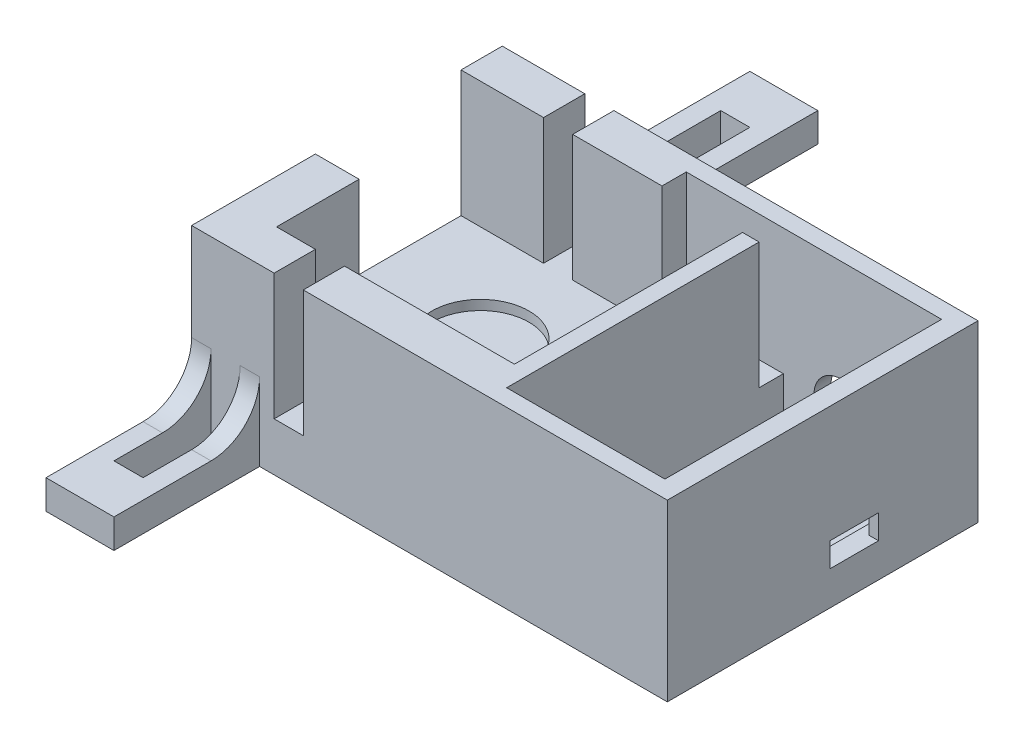
SolidWorks part; units mm, degrees
ref_plane "前视基准面" through (0, 0, 0) normal (0, 0, 1) x (1, 0, 0)
ref_plane "上视基准面" through (0, 0, 0) normal (0, 1, 0) x (1, 0, 0)
ref_plane "右视基准面" through (0, 0, 0) normal (1, 0, 0) x (0, 0, -1)
sketch "草图1" plane through (0, 0, 0) normal (0, 1, 0) x (1, 0, 0)
  line L21 (0, 0) -> (49, 0)
  line L22 (0, 0) -> (0, 32)
  line L23 (0, 32) -> (49, 32)
  line L24 (49, 0) -> (49, 32)
  dimension "D1" = 32
  dimension "D2" = 49
extrude "凸台-拉伸2" add sketch "草图1" along normal blind 18
sketch "草图6" plane through (0, 18, 0) normal (0, 1, 0) x (1, 0, 0)
  line L0 (4.5, 32) -> (4.5, 0) construction
  line L1 (49, 32) -> (0, 32) construction
  line L2 (0, 0) -> (49, 0) construction
  line L4 (4.5, 27.75) -> (29, 27.75)
  line L5 (4.5, 27.75) -> (4.5, 4.25)
  line L6 (4.5, 4.25) -> (29, 4.25)
  line L7 (29, 27.75) -> (29, 4.25)
  line L8 (49, 0) -> (49, 32) construction
  line L9 (4.5, 30) -> (47, 30) construction
  line L10 (4.5, 30) -> (4.5, 2) construction
  line L11 (4.5, 2) -> (47, 2) construction
  line L12 (47, 30) -> (47, 2) construction
  dimension "D1" = 4.5
  dimension "D2" = 23.5
  dimension "D3" = 24.5
  dimension "D4" = 2.25
  dimension "D5" = 2
  dimension "D6" = 2
  dimension "D7" = 2
extrude "切除-拉伸1" cut sketch "草图6" against normal blind 13
sketch "草图7" plane through (0, 18, 0) normal (0, 1, 0) x (1, 0, 0)
  line L0 (49, 0) -> (49, 32) construction
  line L1 (30.7, 30.25) -> (47, 30.25)
  line L2 (30.7, 30.25) -> (30.7, 1.75)
  line L3 (30.7, 1.75) -> (47, 1.75)
  line L4 (47, 30.25) -> (47, 1.75)
  line L5 (49, 32) -> (0, 32) construction
  line L6 (0, 0) -> (49, 0) construction
  dimension "D1" = 2
  dimension "D2" = 1.75
  dimension "D3" = 1.75
  dimension "D4" = 16.3
extrude "切除-拉伸2" cut sketch "草图7" against normal blind 16.5
sketch "草图8" plane through (0, 18, 0) normal (0, 1, 0) x (1, 0, 0)
  line L0 (49, 32) -> (0, 32) construction
  line L1 (8.5, 32) -> (11.5, 32)
  line L2 (8.5, 32) -> (8.5, 0)
  line L3 (8.5, 0) -> (11.5, 0)
  line L4 (11.5, 32) -> (11.5, 0)
  line L5 (0, 0) -> (49, 0) construction
  dimension "D1" = 3
  dimension "D2" = 4
extrude "切除-拉伸3" cut sketch "草图8" against normal blind 13
sketch "草图12" plane through (4.5, 0, 0) normal (1, 0, 0) x (0, 0, -1)
  line L1 (27.75, 5) -> (12.75, 5)
  line L2 (27.75, 5) -> (27.75, 18)
  line L3 (27.75, 18) -> (12.75, 18)
  line L4 (27.75, 18) -> (4.25, 18)
  line L5 (4.25, 18) -> (4.25, 5)
  line L6 (4.25, 5) -> (27.75, 5)
  line L7 (27.75, 5) -> (27.75, 18)
  line L8 (27.75, 18) -> (4.25, 18) construction
  line L9 (4.25, 18) -> (4.25, 5) construction
  line L10 (4.25, 5) -> (27.75, 5) construction
  line L11 (27.75, 5) -> (27.75, 18) construction
  line L12 (12.75, 5) -> (12.75, 18)
  dimension "D2" = 15
  dimension "D1" = 0
extrude "切除-拉伸5" cut sketch "草图12" against normal through all
sketch "草图13" plane through (0, 18, 0) normal (0, 1, 0) x (1, 0, 0)
  line L0 (29, 27.75) -> (11.5, 27.75) construction
  line L1 (30.7, 30.25) -> (20.7, 30.25)
  line L2 (30.7, 30.25) -> (30.7, 27.75)
  line L3 (30.7, 27.75) -> (20.7, 27.75)
  line L4 (20.7, 30.25) -> (20.7, 27.75)
  dimension "D1" = 10
extrude "切除-拉伸6" cut sketch "草图13" against normal blind 13
sketch "草图14" plane through (0, 0, -1.75) normal (0, 0, -1) x (-1, 0, 0)
  line L0 (-41.05, 4.7) -> (-36.65, 4.7) construction
  line L1 (-41.05, 7.5) -> (-36.65, 7.5)
  line L2 (-41.05, 1.9) -> (-36.65, 1.9)
  line L3 (-38.85, 1.5) -> (-38.85, 18) construction
  line L4 (-30.7, 18) -> (-47, 18)
  line L5 (-47, 18) -> (-47, 1.5)
  line L6 (-47, 1.5) -> (-30.7, 1.5)
  line L7 (-30.7, 1.5) -> (-30.7, 18)
  line L8 (-30.7, 18) -> (-47, 18) construction
  line L9 (-47, 18) -> (-47, 1.5) construction
  line L10 (-47, 1.5) -> (-30.7, 1.5) construction
  line L11 (-30.7, 1.5) -> (-30.7, 18) construction
  arc A0 (-41.05, 7.5) -> (-41.05, 1.9) centre (-41.05, 4.7) ccw
  arc A1 (-36.65, 1.9) -> (-36.65, 7.5) centre (-36.65, 4.7) ccw
  point P6 (-38.85, 4.7)
  point P11 (-43.85, 4.7)
  point P12 (-33.85, 4.7)
  dimension "D2" = 10
  dimension "D3" = 2.8
  dimension "D4" = 3.2
  dimension "D1" = 0
extrude "切除-拉伸7" cut sketch "草图14" along normal through all
sketch "草图15" plane through (0, 0, 0) normal (0, -1, 0) x (-1, 0, 0)
  line L1 (0, 32) -> (-7, 32)
  line L2 (0, 32) -> (0, 57.5)
  line L3 (0, 57.5) -> (-7, 57.5)
  line L4 (-7, 32) -> (-7, 57.5)
  dimension "D1" = 7
  dimension "D2" = 25.5
extrude "凸台-拉伸3" add sketch "草图15" against normal blind 3
sketch "草图16" plane through (0, 0, 0) normal (0, -1, 0) x (1, 0, 0)
  line L1 (0, 0) -> (7, 0)
  line L2 (0, 0) -> (0, 15)
  line L3 (0, 15) -> (7, 15)
  line L4 (7, 0) -> (7, 15)
  dimension "D1" = 7
  dimension "D2" = 15
extrude "凸台-拉伸4" add sketch "草图16" against normal blind 3
fillet "圆角1" radius 5 2 edges at (3.5, 3, -32) (3.5, 3, 0)
sketch "草图17" plane through (0, 0, 0) normal (0, -1, 0) x (-1, 0, 0)
  line L0 (-3.5, -15) -> (-3.5, 57.5) construction
  line L1 (-7, -15) -> (0, -15) construction
  line L2 (0, 57.5) -> (-7, 57.5) construction
  line L3 (-7, 0) -> (-49, 0) construction
  line L4 (-2, -10) -> (-5, -10)
  line L5 (-2, -10) -> (-2, 0)
  line L6 (-2, 0) -> (-5, 0)
  line L7 (-5, -10) -> (-5, 0)
  line L8 (-2, -10) -> (-5, 0) construction
  line L9 (-2, 0) -> (-5, -10) construction
  line L10 (-2, 52.5) -> (-5, 52.5)
  line L11 (-2, 52.5) -> (-2, 32)
  line L12 (-2, 32) -> (-5, 32)
  line L13 (-5, 52.5) -> (-5, 32)
  line L14 (-2, 52.5) -> (-5, 32) construction
  line L15 (-2, 32) -> (-5, 52.5) construction
  line L16 (-49, 32) -> (-7, 32) construction
  point P6 (-3.5, -5)
  point P11 (-3.5, 42.25)
  dimension "D1" = 5
  dimension "D2" = 3
  dimension "D3" = 5
  dimension "D4" = 0
  dimension "D5" = 0
extrude "切除-拉伸8" cut sketch "草图17" against normal through all
sketch "草图19" plane through (0, 5, 0) normal (0, 1, 0) x (1, 0, 0)
  line L0 (0, 12.75) -> (0, 27.75) construction
  line L1 (20.7, 27.75) -> (11.5, 27.75) construction
  circle A0 centre (12, 17.75) radius 5
  dimension "D1" = 12
  dimension "D2" = 10
extrude "切除-拉伸9" cut sketch "草图19" against normal blind 1
sketch "草图20" plane through (47, 0, 0) normal (-1, 0, 0) x (0, 0, 1)
  line L5 (-23.75, 3.5) -> (-14.75, 3.5)
  line L6 (-23.75, 3.5) -> (-23.75, 6)
  line L7 (-21.75, 6) -> (-16.75, 6)
  line L8 (-1.75, 18) -> (-30.25, 18)
  line L9 (-30.25, 18) -> (-30.25, 1.5)
  line L10 (-30.25, 1.5) -> (-1.75, 1.5)
  line L11 (-1.75, 1.5) -> (-1.75, 18)
  line L12 (-1.75, 18) -> (-30.25, 18) construction
  line L13 (-30.25, 18) -> (-30.25, 1.5) construction
  line L14 (-30.25, 1.5) -> (-1.75, 1.5) construction
  line L15 (-1.75, 1.5) -> (-1.75, 18) construction
  line L16 (-14.75, 3.5) -> (-14.75, 6)
  line L17 (-23.75, 3.5) -> (-14.75, 6) construction
  line L18 (-23.75, 6) -> (-14.75, 3.5) construction
  line L20 (-23.75, 6) -> (-23.75, 8)
  line L21 (-23.75, 8) -> (-21.75, 8)
  line L22 (-21.75, 6) -> (-21.75, 8)
  line L24 (-14.75, 6) -> (-14.75, 8)
  line L25 (-14.75, 8) -> (-16.75, 8)
  line L26 (-16.75, 6) -> (-16.75, 8)
  point P2 (-19.25, 4.75)
  dimension "D2" = 2
  dimension "D3" = 2.5
  dimension "D4" = 9
  dimension "D5" = 11
  dimension "D6" = 2
  dimension "D7" = 2
  dimension "D8" = 5
  dimension "D9" = 2
  dimension "D1" = 0
extrude "切除-拉伸10" cut sketch "草图20" against normal blind 1
sketch "草图25" plane through (48, 0, 0) normal (-1, 0, 0) x (0, 0, 1)
  line L0 (-19.25, 3.5) -> (-19.25, 6) construction
  line L2 (-21.75, 6) -> (-16.75, 6)
  line L3 (-21.75, 6) -> (-21.75, 3.5)
  line L4 (-21.75, 3.5) -> (-16.75, 3.5)
  line L5 (-16.75, 6) -> (-16.75, 3.5)
  line L8 (-14.75, 3.5) -> (-14.75, 8)
  line L9 (-14.75, 8) -> (-16.75, 8)
  line L10 (-16.75, 8) -> (-16.75, 6)
  line L11 (-16.75, 6) -> (-21.75, 6)
  line L12 (-21.75, 6) -> (-21.75, 8)
  line L13 (-21.75, 8) -> (-23.75, 8)
  line L14 (-23.75, 8) -> (-23.75, 3.5)
  line L15 (-23.75, 3.5) -> (-14.75, 3.5)
  line L16 (-14.75, 3.5) -> (-14.75, 8) construction
  line L17 (-14.75, 8) -> (-16.75, 8) construction
  line L18 (-16.75, 8) -> (-16.75, 6) construction
  line L19 (-16.75, 6) -> (-21.75, 6) construction
  line L20 (-21.75, 6) -> (-21.75, 8) construction
  line L21 (-21.75, 8) -> (-23.75, 8) construction
  line L22 (-23.75, 8) -> (-23.75, 3.5) construction
  line L23 (-23.75, 3.5) -> (-14.75, 3.5) construction
  dimension "D2" = 2.5
  dimension "D1" = 0
extrude "切除-拉伸13" cut sketch "草图25" against normal through all
